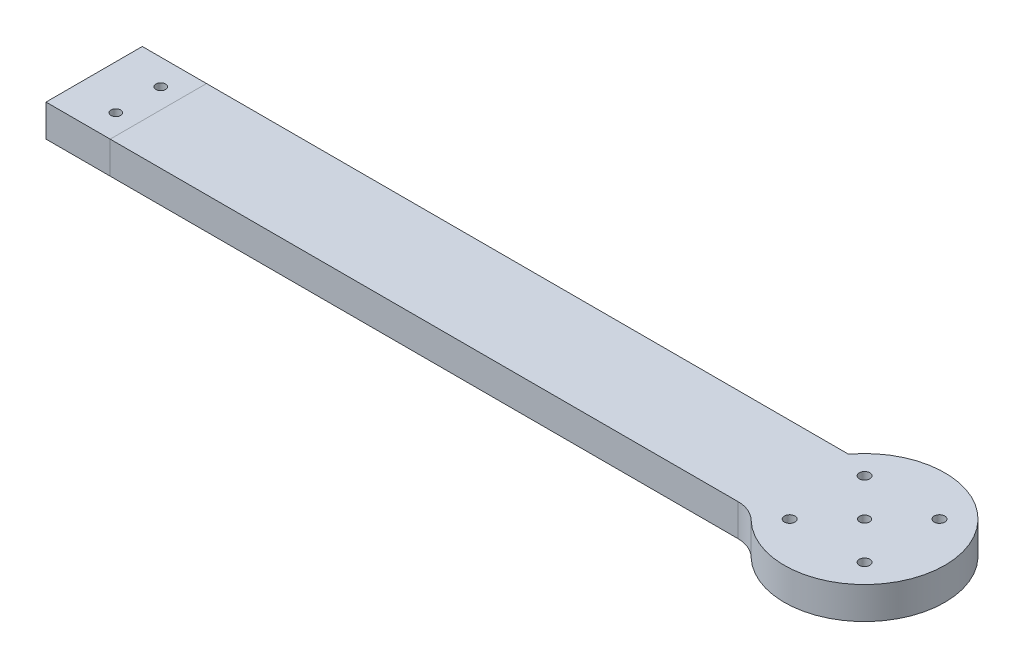
SolidWorks part; units mm, degrees
material "ABS"
ref_plane "Front Plane" through (0, 0, 0) normal (0, 0, 1) x (1, 0, 0)
ref_plane "Top Plane" through (0, 0, 0) normal (0, 1, 0) x (1, 0, 0)
ref_plane "Right Plane" through (0, 0, 0) normal (1, 0, 0) x (0, 0, -1)
sketch "Sketch2" plane through (0, 0, 0) normal (0, 1, 0) x (1, 0, 0)
  line L0 (220, 15) -> (0, 15) construction
  line L1 (0, 0) -> (200, 0)
  line L2 (0, 0) -> (0, 30)
  line L3 (0, 30) -> (200, 30)
  arc A0 (200, 30) -> (200, 0) centre (220, 15) cw
  dimension "D3" = 25
  dimension "D1" = 200
  dimension "D2" = 30
extrude "Boss-Extrude1" add sketch "Sketch2" along normal blind 10
sketch "Sketch4" plane through (0, 0, 0) normal (-1, 0, 0) x (0, 0, 1)
  line L4 (-30, 0) -> (0, 0)
  line L5 (0, 0) -> (0, 10)
  line L6 (0, 10) -> (-30, 10)
  line L7 (-30, 10) -> (-30, 0)
  line L8 (-30, 0) -> (0, 0)
  line L9 (0, 0) -> (0, 10)
  line L10 (0, 10) -> (-30, 10)
  line L11 (-30, 10) -> (-30, 0)
  dimension "D1" = 0
extrude "Boss-Extrude3" add sketch "Sketch4" along normal blind 20 separate body
sketch "Sketch5" plane through (0, 10, 0) normal (0, 1, 0) x (1, 0, 0)
  line L0 (-6.25, 8) -> (-6.25, 0) construction
  line L3 (-6.25, 22) -> (-6.25, 30) construction
  line L6 (0, 30) -> (0, 0) construction
  line L7 (-20, 0) -> (0, 0) construction
  line L10 (-20, 30) -> (0, 30) construction
  line L11 (-6.25, 22) -> (0, 22) construction
  line L12 (0, 0) -> (0, 30) construction
  line L13 (-6.25, 8) -> (0, 8) construction
  circle A4 centre (-6.25, 22) radius 1.5
  circle A5 centre (-6.25, 8) radius 1.5
  dimension "D2" = 8
  dimension "D3" = 6.25
  dimension "D1" = 3
extrude "Cut-Extrude1" cut sketch "Sketch5" against normal up to surface (10 mm away) up to face at (-10, 0, -15)
sketch "Sketch6" plane through (0, 10, 0) normal (0, 1, 0) x (1, 0, 0)
  line L0 (220, 40) -> (220, -10) construction
  line L1 (208.3327, 26.6673) -> (231.6673, 3.3327) construction
  line L2 (231.6673, 26.6673) -> (208.3327, 3.3327) construction
  arc A0 (200, 0) -> (200, 30) centre (220, 15) ccw construction
  circle A1 centre (231.6673, 26.6673) radius 1.65
  circle A2 centre (231.6673, 3.3327) radius 1.65
  circle A3 centre (208.3327, 3.3327) radius 1.65
  circle A4 centre (208.3327, 26.6673) radius 1.65
  circle A5 centre (220, 15) radius 1.55
  point P9 (220, 15)
  point P12 (220, 15)
  dimension "D4" = 4
  dimension "D5" = 3.3
  dimension "D6" = 3.1
  dimension "D1" = 33
  dimension "D2" = 90
  dimension "D3" = 45
extrude "Drone Mount Holes" cut sketch "Sketch6" against normal up to surface (10 mm away) up to face at (111.25, 0, -15)
fillet "Fillet2" radius 10 1 edges at (200, 5, 0)
